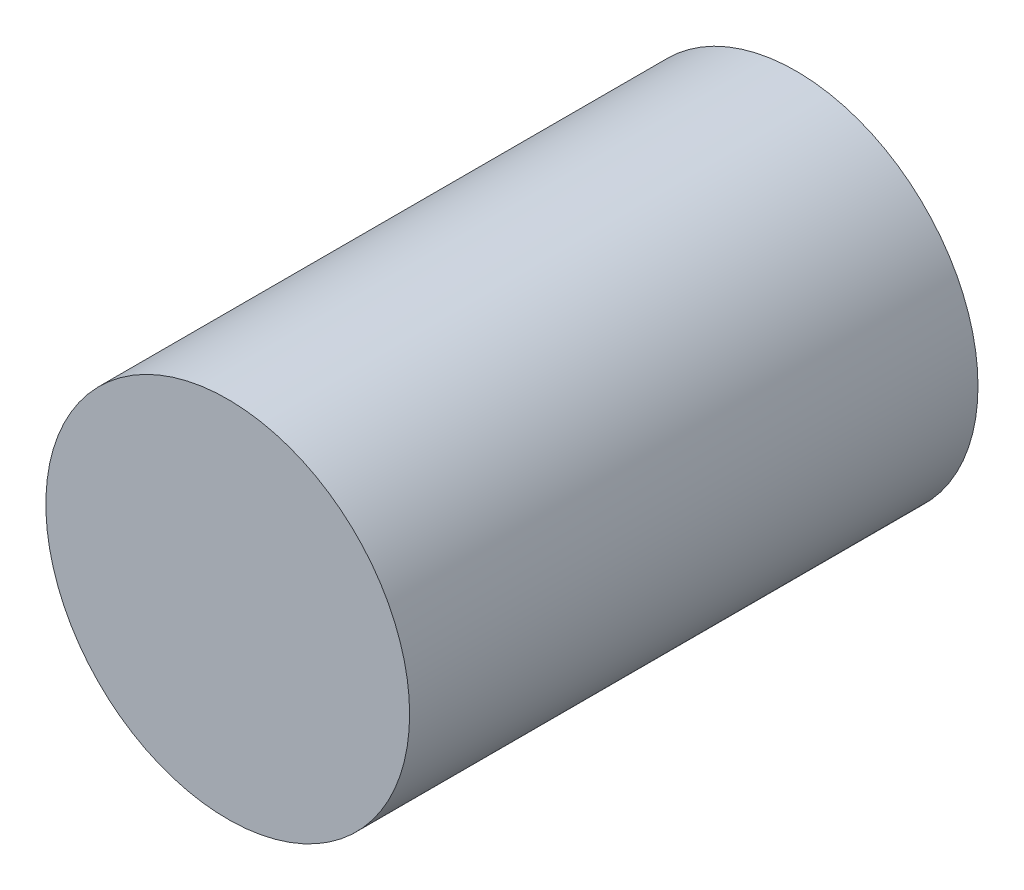
SolidWorks part; units mm, degrees
ref_plane "Front Plane" through (0, 0, 0) normal (0, 0, 1) x (1, 0, 0)
ref_plane "Top Plane" through (0, 0, 0) normal (0, 1, 0) x (1, 0, 0)
ref_plane "Right Plane" through (0, 0, 0) normal (1, 0, 0) x (0, 0, -1)
sketch "Sketch1" plane through (0, 0, 0) normal (0, 0, 1) x (1, 0, 0)
  circle A0 centre (0, 0) radius 4.064
  circle A1 centre (0, 0) radius 4.064
  dimension "D1" = 8.128
  dimension "D2" = 8.128
extrude "Boss-Extrude1" add sketch "Sketch1" along normal blind 12.7 contours A1
